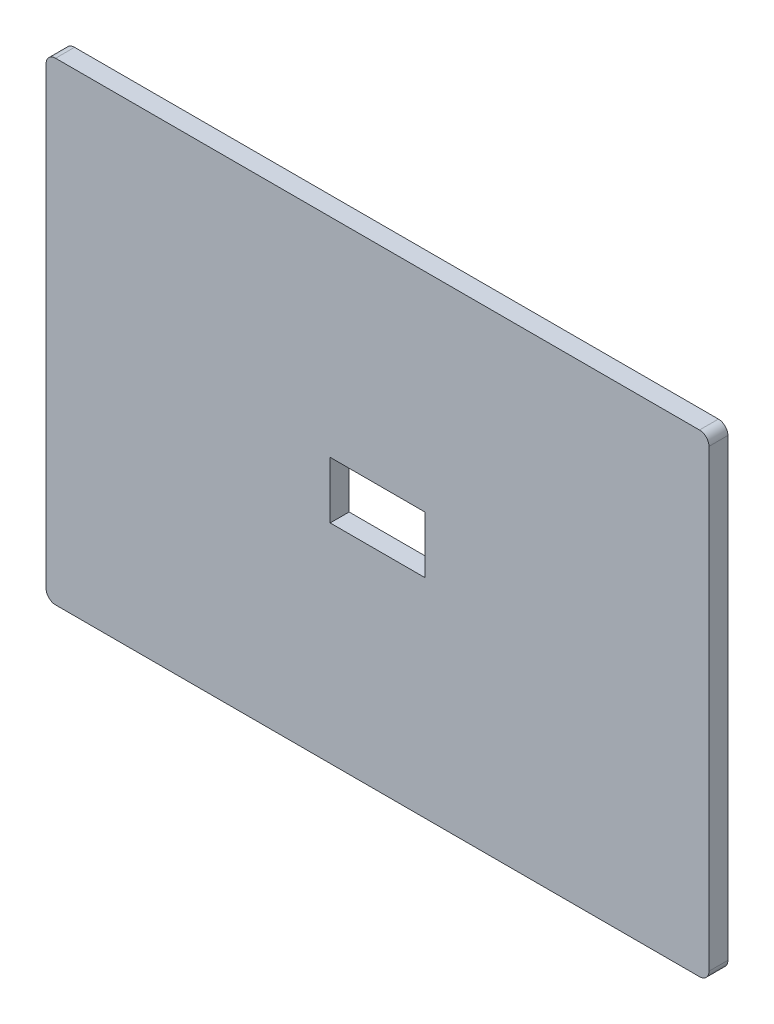
SolidWorks part; units mm, degrees
ref_plane "Vorne" through (0, 0, 0) normal (0, 0, 1) x (1, 0, 0)
ref_plane "Oben" through (0, 0, 0) normal (0, 1, 0) x (1, 0, 0)
ref_plane "Rechts" through (0, 0, 0) normal (1, 0, 0) x (0, 0, -1)
ref_plane "E_Boden" through (0, 1, 0) normal (0, 1, 0) x (1, 0, 0)
sketch "Skizze1" plane through (0, 0, 0) normal (0, 0, 1) x (1, 0, 0)
  line L0 (-20.2005, 0) -> (23.2167, 0) construction
  line L1 (0, -7.2428) -> (0, 9.7431) construction
  line L3 (-175, 125) -> (175, 125)
  line L4 (-175, 125) -> (-175, -125)
  line L5 (-175, -125) -> (175, -125)
  line L6 (175, 125) -> (175, -125)
  dimension "D1" = 350
  dimension "D2" = 250
extrude "Aufsatz-Linear austragen1" add sketch "Skizze1" along normal blind 10
fillet "Verrundung1" radius 5 4 edges at (-175, -125, 5) (175, -125, 5) (175, 125, 5) (-175, 125, 5)
sketch "Skizze3" plane through (0, 0, 10) normal (0, 0, 1) x (1, 0, 0)
  line L0 (-197.8153, 0) -> (213.6577, 0) construction
  line L1 (0, -183.9789) -> (0, 229.6789) construction
  line L2 (-175, 120) -> (-175, -120) construction
  line L3 (175, -120) -> (175, 120) construction
  line L4 (-170, -125) -> (170, -125) construction
  line L5 (170, 125) -> (-170, 125) construction
  line L7 (-25, -15) -> (25, -15)
  line L8 (-25, -15) -> (-25, 15)
  line L9 (-25, 15) -> (25, 15)
  line L10 (25, -15) -> (25, 15)
  dimension "D1" = 30
  dimension "D2" = 50
extrude "Schnitt-Linear austragen1" cut sketch "Skizze3" against normal through all
